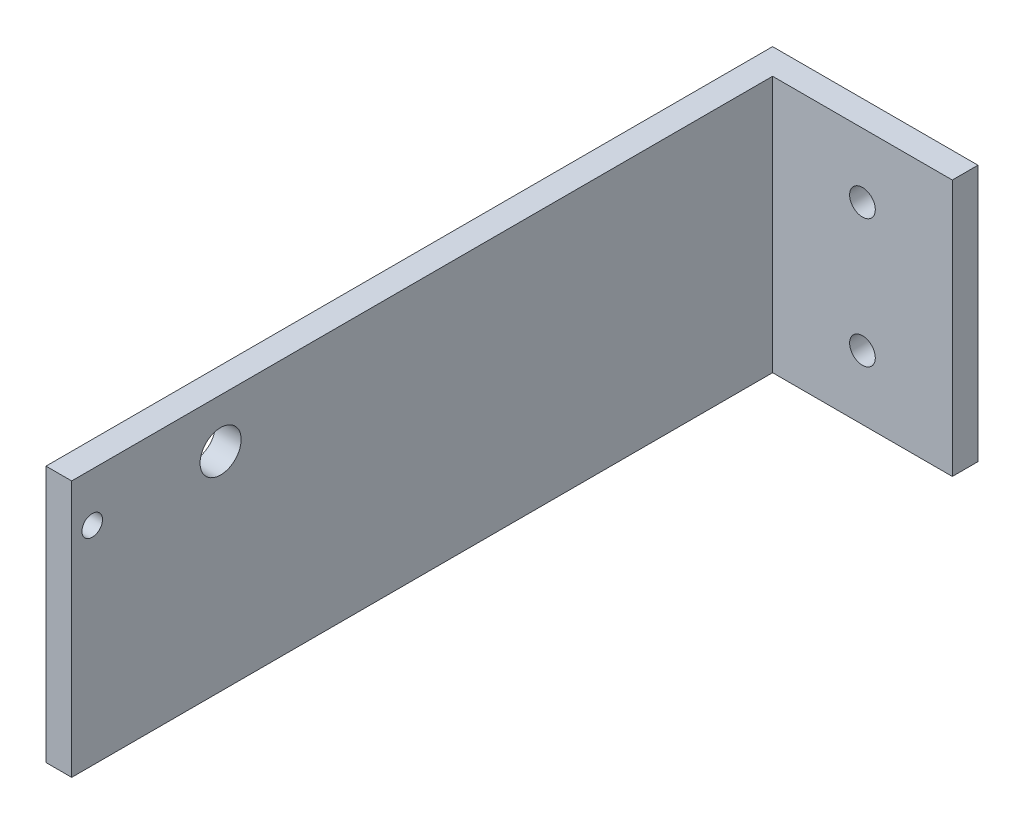
SolidWorks part; units mm, degrees
ref_plane "Front Plane" through (0, 0, 0) normal (0, 0, 1) x (1, 0, 0)
ref_plane "Top Plane" through (0, 0, 0) normal (0, 1, 0) x (1, 0, 0)
ref_plane "Right Plane" through (0, 0, 0) normal (1, 0, 0) x (0, 0, -1)
sketch "Sketch3" plane through (0, 0, 0) normal (0, 1, 0) x (1, 0, 0)
  line L0 (0, 0) -> (5, 0)
  line L1 (5, 0) -> (5, 136.5)
  line L2 (5, 136.5) -> (40, 136.5)
  line L3 (40, 136.5) -> (40, 141.5)
  line L4 (40, 141.5) -> (0, 141.5)
  line L5 (0, 141.5) -> (0, 0)
  point P3 (40, 139)
  dimension "D1" = 5
  dimension "D2" = 5
  dimension "D3" = 40
  dimension "D4" = 141.5
extrude "Boss-Extrude2" add sketch "Sketch3" along normal mid plane 50
sketch "Sketch4" plane through (5, 0, 0) normal (1, 0, 0) x (0, 0, -1)
  line L0 (0, 25) -> (136.5, 25) construction
  line L1 (0, 25) -> (0, -25) construction
  circle A0 centre (4, 15.5) radius 2
  circle A1 centre (29, 15.5) radius 4
  dimension "D1" = 4
  dimension "D2" = 8
  dimension "D3" = 25
  dimension "D4" = 9.5
  dimension "D5" = 4
extrude "Cut-Extrude2" cut sketch "Sketch4" against normal up to next
sketch "Sketch1" plane through (0, 0, 0) normal (0, 0, 1) x (1, 0, 0)
  line L0 (0, 342) -> (0, 0)
  line L1 (0, 0) -> (-30, 0)
  line L2 (-30, 0) -> (-30, 2)
  line L3 (-30, 2) -> (-2, 2)
  line L4 (-2, 2) -> (-2, 342)
  line L5 (-2, 342) -> (0, 342)
  dimension "D1" = 2
  dimension "D2" = 2
  dimension "D3" = 342
  dimension "D4" = 30
extrude "Boss-Extrude1" [suppressed] add sketch "Sketch1" along normal mid plane 37
sketch "Sketch2" [suppressed] plane through (-2, 0, 0) normal (-1, 0, 0) x (0, 0, 1)
  line L0 (18.5, 342) -> (-18.5, 342) construction
  line L2 (-18.5, 342) -> (-18.5, 2) construction
  circle A0 centre (-11, 332.5) radius 4
  circle A1 centre (14, 332.5) radius 2
  dimension "D1" = 8
  dimension "D5" = 4
  dimension "D2" = 9.5
  dimension "D3" = 7.5
  dimension "D4" = 25
extrude "Cut-Extrude1" [suppressed] cut sketch "Sketch2" against normal up to next
sketch "Sketch5" plane through (0, 0, -136.5) normal (0, 0, 1) x (1, 0, 0)
  line L0 (0, 0) -> (37.8103, 0) construction
  line L2 (40, 25) -> (40, -25) construction
  circle A0 centre (22.5, 12.5) radius 2.5
  circle A1 centre (22.5, -12.5) radius 2.5
  dimension "D1" = 5
  dimension "D2" = 17.5
  dimension "D3" = 25
extrude "Cut-Extrude3" cut sketch "Sketch5" against normal up to next
